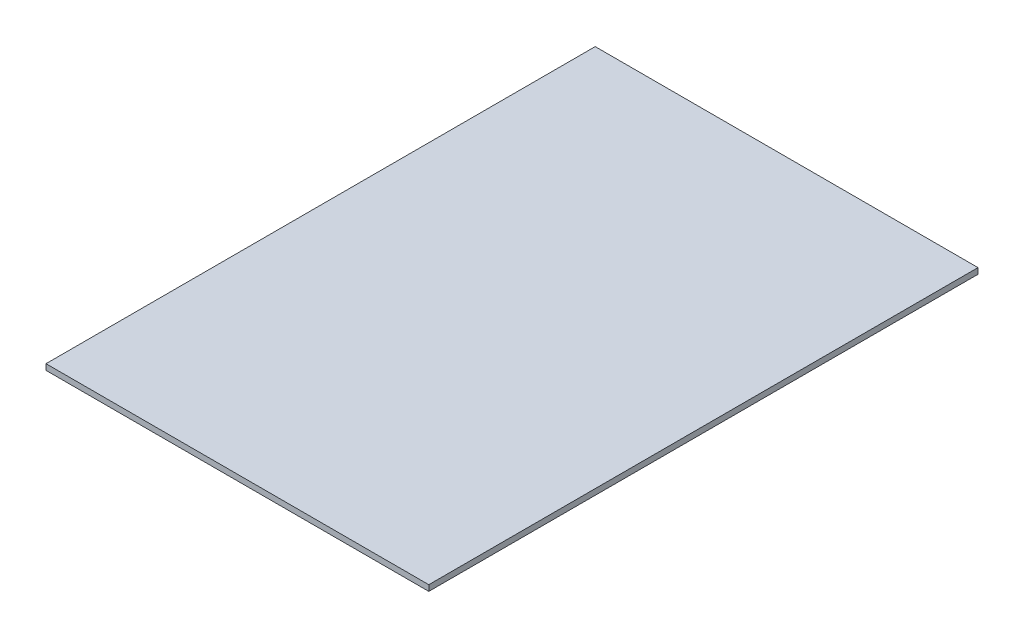
SolidWorks part; units mm, degrees
ref_plane "Plano frontal" through (0, 0, 0) normal (0, 0, 1) x (1, 0, 0)
ref_plane "Plano superior" through (0, 0, 0) normal (0, 1, 0) x (1, 0, 0)
ref_plane "Plano direito" through (0, 0, 0) normal (1, 0, 0) x (0, 0, -1)
sketch "Esboço1" plane through (0, 0, 0) normal (0, 1, 0) x (1, 0, 0)
  line L1 (-115, 165) -> (115, 165)
  line L2 (-115, 165) -> (-115, -165)
  line L3 (-115, -165) -> (115, -165)
  line L4 (115, 165) -> (115, -165)
  line L5 (-115, 165) -> (115, -165) construction
  line L6 (-115, -165) -> (115, 165) construction
  point P0 (0, 0)
  dimension "D1" = 230
  dimension "D2" = 330
extrude "Ressalto-extrusão1" add sketch "Esboço1" along normal blind 3.5
